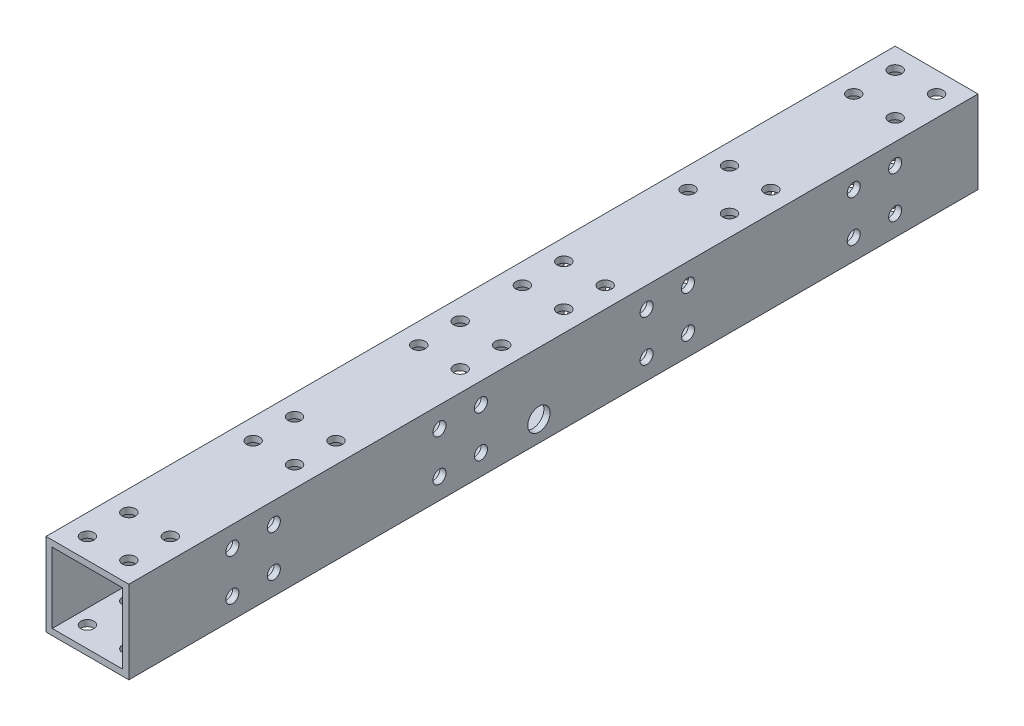
SolidWorks part; units mm, degrees
ref_plane "前视基准面" through (0, 0, 0) normal (0, 0, 1) x (1, 0, 0)
ref_plane "上视基准面" through (0, 0, 0) normal (0, 1, 0) x (1, 0, 0)
ref_plane "右视基准面" through (0, 0, 0) normal (1, 0, 0) x (0, 0, -1)
other "Configuration Table"
sketch "草图1" plane through (0, 0, 0) normal (0, 0, 1) x (1, 0, 0)
  line L4 (0, 0) -> (20, 0)
  line L5 (0, 0) -> (0, -20)
  line L6 (0, -20) -> (20, -20)
  line L7 (20, 0) -> (20, -20)
  dimension "D1" = 20
  dimension "D2" = 20
extrude "拉伸-薄壁1" add sketch "草图1" along normal blind 205 thin
sketch "草图2" plane through (0, 0, 0) normal (-1, 0, 0) x (0, 0, 1)
  line L0 (205, -20) -> (0, -20) construction
  line L1 (175, 0) -> (175, -20) construction
  line L2 (0, 0) -> (0, -20) construction
  line L3 (205, 0) -> (0, 0) construction
  line L4 (205, -10) -> (175, -10) construction
  line L5 (205, 0) -> (205, -20) construction
  circle A0 centre (106, -15) radius 2.7
  circle A1 centre (180, -5) radius 1.575
  circle A2 centre (180, -15) radius 1.575
  circle A3 centre (170, -15) radius 1.575
  circle A4 centre (170, -5) radius 1.575
  circle A6 centre (120, -5) radius 1.575
  circle A7 centre (130, -5) radius 1.575
  circle A8 centre (120, -15) radius 1.575
  circle A9 centre (130, -15) radius 1.575
  circle A10 centre (70, -5) radius 1.575
  circle A11 centre (80, -5) radius 1.575
  circle A12 centre (70, -15) radius 1.575
  circle A13 centre (80, -15) radius 1.575
  circle A14 centre (20, -5) radius 1.575
  circle A15 centre (30, -5) radius 1.575
  circle A16 centre (20, -15) radius 1.575
  circle A17 centre (30, -15) radius 1.575
  dimension "D1" = 5.4
  dimension "D5" = 3.15
  dimension "D2" = 5
  dimension "D3" = 106
  dimension "D4" = 30
  dimension "D6" = 5
  dimension "D7" = 5
  dimension "D8" = 40
extrude "切除-拉伸1" cut sketch "草图2" against normal through all
sketch "草图3" plane through (0, 0, 0) normal (0, 1, 0) x (1, 0, 0)
  line L0 (0, -102.5) -> (20, -102.5) construction
  line L1 (0, -205) -> (0, 0) construction
  line L2 (20, -205) -> (20, 0) construction
  line L3 (0, -10) -> (20, -10) construction
  line L4 (20, 0) -> (0, 0) construction
  line L5 (10, 0) -> (10, -10) construction
  line L6 (10, -205) -> (10, -195) construction
  line L7 (0, -195) -> (20, -195) construction
  line L8 (0, -185) -> (20, -185) construction
  line L9 (20, -205) -> (0, -205) construction
  circle A0 centre (5, -5) radius 1.575
  circle A1 centre (15, -5) radius 1.575
  circle A2 centre (15, -15) radius 1.575
  circle A3 centre (5, -15) radius 1.575
  circle A4 centre (5, -190) radius 1.575
  circle A5 centre (15, -190) radius 1.575
  circle A6 centre (15, -200) radius 1.575
  circle A7 centre (5, -200) radius 1.575
  circle A8 centre (5, -150) radius 1.575
  circle A9 centre (15, -150) radius 1.575
  circle A10 centre (5, -160) radius 1.575
  circle A11 centre (15, -160) radius 1.575
  circle A12 centre (5, -110) radius 1.575
  circle A13 centre (15, -110) radius 1.575
  circle A14 centre (5, -120) radius 1.575
  circle A15 centre (15, -120) radius 1.575
  circle A16 centre (15, -85) radius 1.575
  circle A17 centre (5, -85) radius 1.575
  circle A18 centre (15, -95) radius 1.575
  circle A19 centre (5, -95) radius 1.575
  circle A20 centre (15, -45) radius 1.575
  circle A21 centre (5, -45) radius 1.575
  circle A22 centre (15, -55) radius 1.575
  circle A23 centre (5, -55) radius 1.575
  point P10 (10, 0)
  dimension "D3" = 3.15
  dimension "D1" = 10
  dimension "D2" = 5
  dimension "D4" = 5
  dimension "D5" = 20
  dimension "D6" = 40
extrude "切除-拉伸2" cut sketch "草图3" against normal through all
